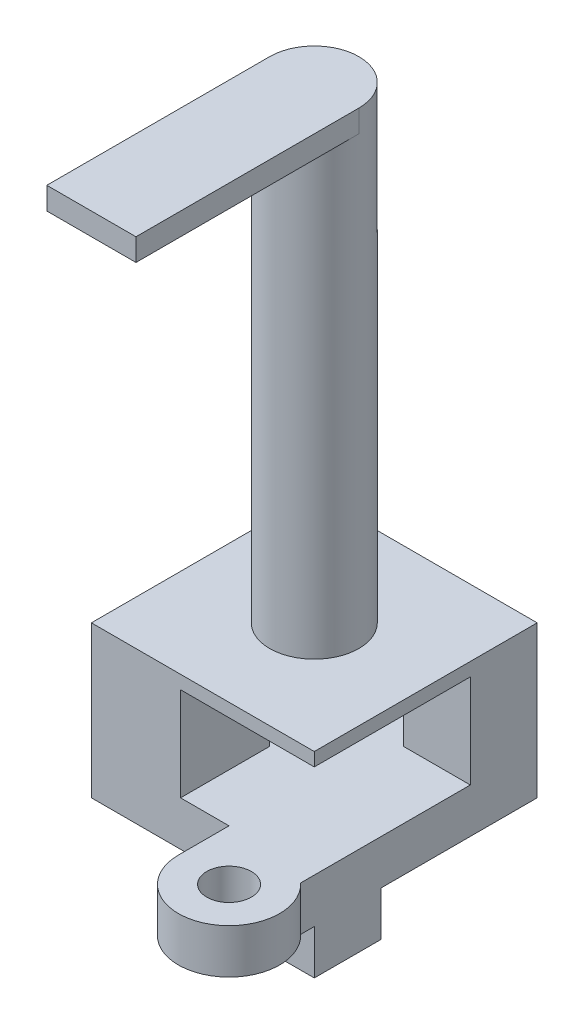
SolidWorks part; units mm, degrees
ref_plane "Front Plane" through (0, 0, 0) normal (0, 0, 1) x (1, 0, 0)
ref_plane "Top Plane" through (0, 0, 0) normal (0, 1, 0) x (1, 0, 0)
ref_plane "Right Plane" through (0, 0, 0) normal (1, 0, 0) x (0, 0, -1)
sketch "Sketch1" plane through (0, 0, 0) normal (0, 1, 0) x (1, 0, 0)
  line L1 (0, 0) -> (30.8761, 0)
  line L2 (0, 0) -> (0, 50)
  line L3 (0, 50) -> (50, 50)
  line L4 (50, 0) -> (50, 50)
  line L6 (9.8747, 47.1916) -> (24.2967, 33.2903)
  line L7 (3.4363, 40.4752) -> (17.9343, 26.6531)
  line L8 (50, 0) -> (50, -3.0636)
  line L9 (30.8761, -11.3627) -> (30.8761, 0)
  arc A2 (17.9343, 26.6531) -> (24.2967, 33.2903) centre (21.1064, 29.9804) ccw
  arc A3 (9.8747, 47.1916) -> (3.4363, 40.4752) centre (6.6463, 43.8422) ccw
  arc A5 (30.8761, -11.3627) -> (50, -3.0636) centre (42.2388, -11.3627) ccw
  circle A6 centre (42.2388, -11.3627) radius 5
  dimension "D3" = 10
  dimension "D1" = 50
  dimension "D2" = 50
extrude "Boss-Extrude1" add sketch "Sketch1" along normal blind 10
sketch "Sketch2" plane through (0, 0, 0) normal (0, -1, 0) x (1, 0, 0)
  line L3 (45, -5) -> (35, -5)
  line L4 (35, 0) -> (35, -5)
  line L7 (50, -15) -> (45, -15)
  line L8 (45, -5) -> (45, -15)
  line L20 (50, -15) -> (50, 0)
  line L21 (50, 3.0636) -> (50, -50) construction
  line L22 (50, 0) -> (35, 0)
  dimension "D3" = 10
  dimension "D4" = 10
extrude "Boss-Extrude2" add sketch "Sketch2" along normal blind 10
sketch "Sketch3" plane through (0, 10, 0) normal (0, 1, 0) x (1, 0, 0)
  line L1 (0, 0) -> (20, 0)
  line L2 (0, 0) -> (0, 20)
  line L3 (0, 20) -> (20, 20)
  line L4 (20, 0) -> (20, 20)
  line L5 (50, 50) -> (35, 50)
  line L6 (50, 50) -> (50, 35)
  line L7 (50, 35) -> (35, 35)
  line L8 (35, 50) -> (35, 35)
  dimension "D1" = 20
  dimension "D2" = 20
  dimension "D4" = 15
extrude "Boss-Extrude3" add sketch "Sketch3" along normal blind 21
sketch "Sketch4" plane through (0, 31, 0) normal (0, 1, 0) x (1, 0, 0)
  line L0 (50, 35) -> (50, 50) construction
  line L1 (0, 0) -> (50, 0)
  line L2 (0, 0) -> (0, 50)
  line L3 (0, 50) -> (50, 50)
  line L4 (50, 0) -> (50, 50)
extrude "Boss-Extrude4" add sketch "Sketch4" along normal blind 3
sketch "Sketch5" plane through (0, 34, 0) normal (0, 1, 0) x (1, 0, 0)
  line L0 (0, 0) -> (50, 0) construction
  line L1 (50, -3.0636) -> (50, 35) construction
  circle A0 centre (25, 25) radius 10
  dimension "D1" = 25
  dimension "D2" = 25
  dimension "D3" = 20
extrude "Boss-Extrude5" add sketch "Sketch5" along normal blind 100
sketch "Sketch6" plane through (0, 134, 0) normal (0, 1, 0) x (1, 0, 0)
  line L2 (35, 25) -> (35, -25)
  line L3 (35, -25) -> (15, -25)
  line L4 (15, 25) -> (15, -25)
  arc A0 (35, 25) -> (15, 25) centre (25, 25) ccw
  dimension "D1" = 50
extrude "Boss-Extrude6" add sketch "Sketch6" along normal blind 5
